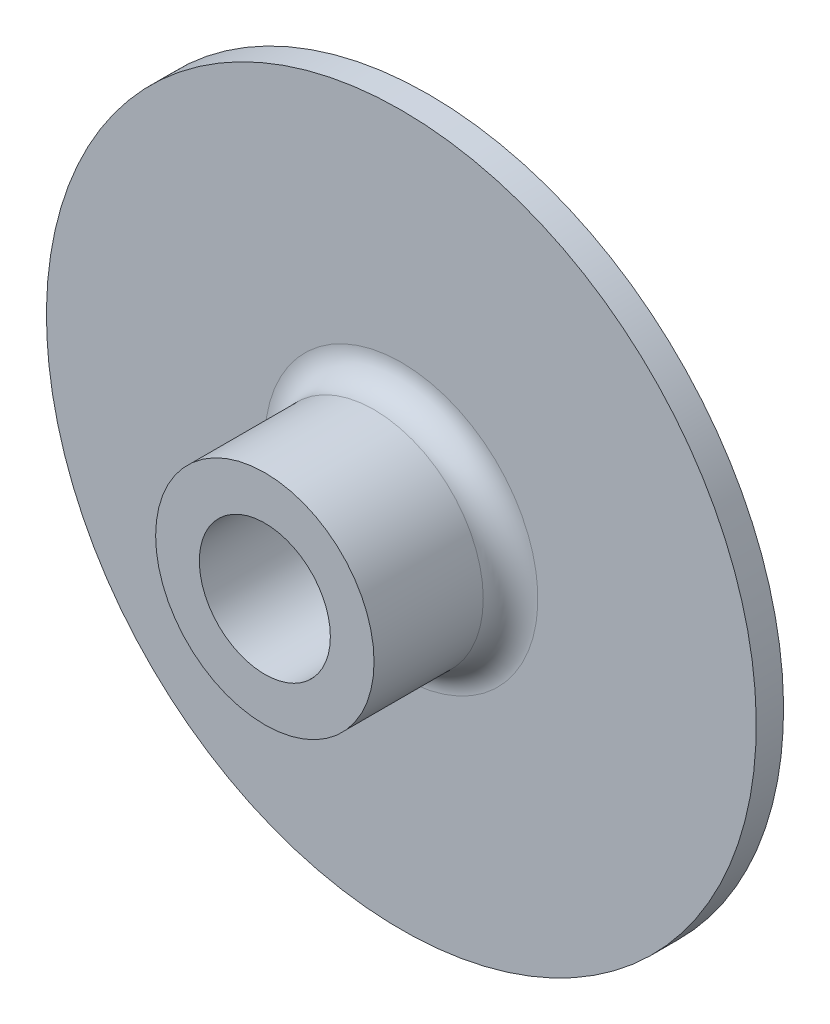
SolidWorks part; units mm, degrees
material "AISI 1020"
ref_plane "Front Plane" through (0, 0, 0) normal (0, 0, 1) x (1, 0, 0)
ref_plane "Top Plane" through (0, 0, 0) normal (0, 1, 0) x (1, 0, 0)
ref_plane "Right Plane" through (0, 0, 0) normal (1, 0, 0) x (0, 0, -1)
sketch "Revolve Sketch" plane through (0, 0, 0) normal (1, 0, 0) x (0, 0, -1)
  line L2 (0, 0) -> (0, 41.275)
  line L3 (0, 41.275) -> (-3.175, 41.275)
  line L4 (-3.175, 12.7) -> (-3.175, 41.275)
  line L5 (0, 0) -> (-19.05, 0)
  line L7 (-3.175, 12.7) -> (-19.05, 12.7)
  line L8 (-19.05, 0) -> (-19.05, 12.7)
  dimension "D1" = 3.175
  dimension "D2" = 41.275
  dimension "D3" = 19.05
  dimension "D4" = 12.7
revolve "Revolve" add sketch "Revolve Sketch" angle 360 about L5
sketch "Cut Sketch" plane through (0, 0, 19.05) normal (0, 0, 1) x (1, 0, 0)
  circle A0 centre (0, 0) radius 7.62
  dimension "D1" = 15.24
extrude "Center Cut" cut sketch "Cut Sketch" against normal through all
sketch "Peripheral Sketch" plane through (0, 0, 3.175) normal (0, 0, 1) x (1, 0, 0)
  line L0 (0, 0) -> (34.925, 0) construction
  circle A0 centre (34.925, 0) radius 3.175
  dimension "D1" = 6.35
  dimension "D2" = 34.925
extrude "Peripheral Cut" [suppressed] cut sketch "Peripheral Sketch" against normal through all
pattern_circular "Circular Cut" [suppressed] count 6 over 360
fillet "Fillet" radius 3.175 1 edges at (0, 12.7, 3.175)
